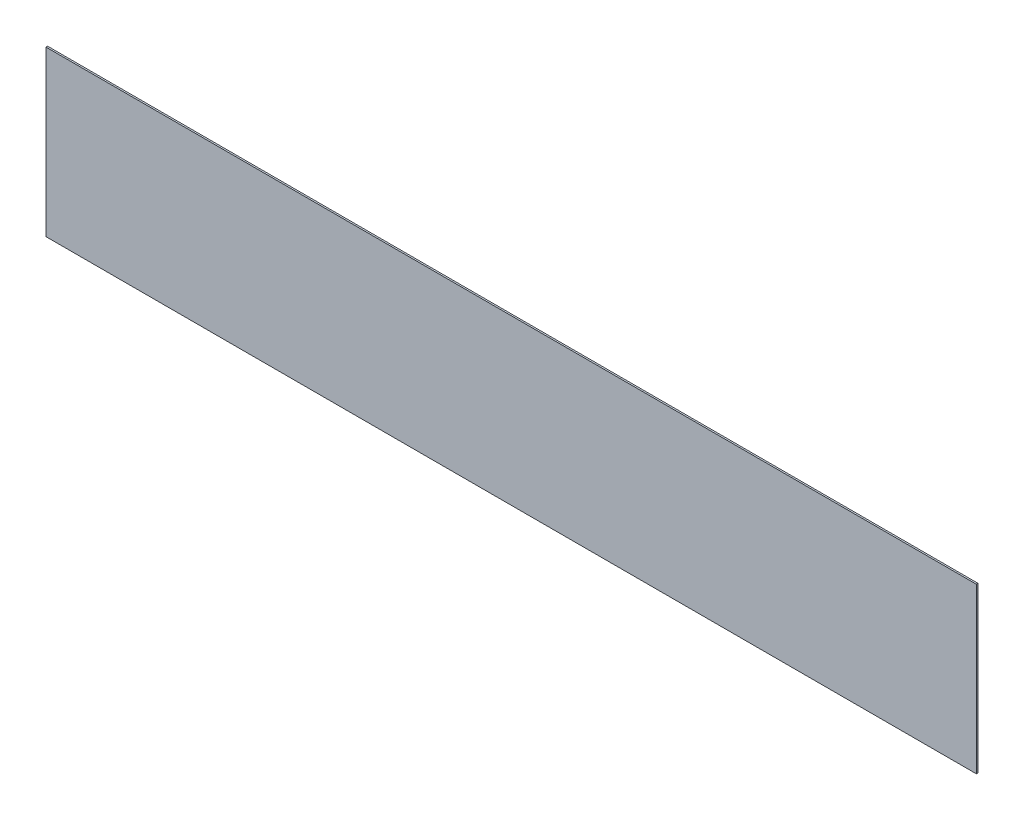
SolidWorks part; units mm, degrees
ref_plane "Alzado" through (0, 0, 0) normal (0, 0, 1) x (1, 0, 0)
ref_plane "Planta" through (0, 0, 0) normal (0, 1, 0) x (1, 0, 0)
ref_plane "Vista lateral" through (0, 0, 0) normal (1, 0, 0) x (0, 0, -1)
sketch "Croquis1" plane through (0, 0, 0) normal (0, 0, 1) x (1, 0, 0)
  line L1 (-564.609, 382.1072) -> (2835.391, 382.1072)
  line L2 (-564.609, 382.1072) -> (-564.609, -217.8928)
  line L3 (-564.609, -217.8928) -> (2835.391, -217.8928)
  line L4 (2835.391, 382.1072) -> (2835.391, -217.8928)
extrude "Saliente-Extruir1" add sketch "Croquis1" along normal blind 6
